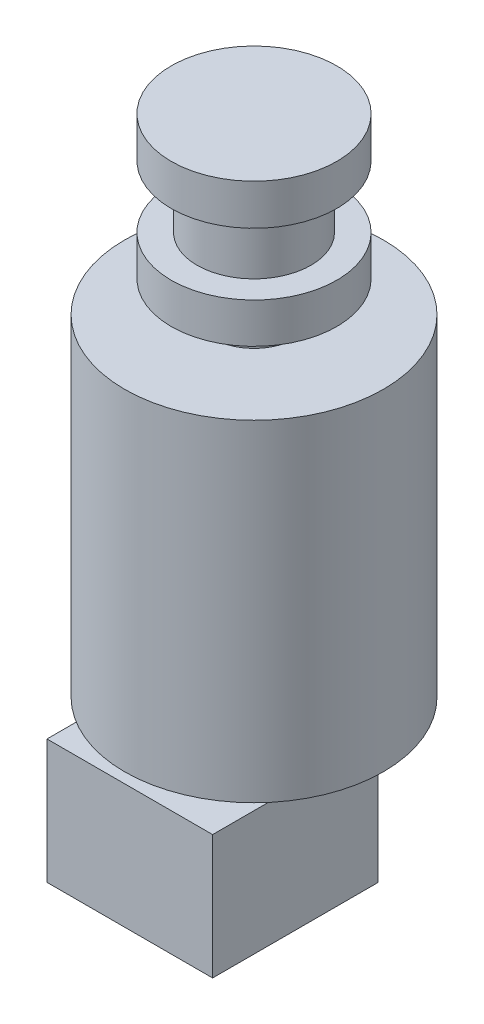
SolidWorks part; units mm, degrees
ref_plane "Plano frontal" through (0, 0, 0) normal (0, 0, 1) x (1, 0, 0)
ref_plane "Plano superior" through (0, 0, 0) normal (0, 1, 0) x (1, 0, 0)
ref_plane "Plano direito" through (0, 0, 0) normal (1, 0, 0) x (0, 0, -1)
sketch "Esboço1" plane through (0, 0, 0) normal (0, 0, 1) x (1, 0, 0)
  line L0 (0, 47.3334) -> (0, -46.585) construction
  line L1 (0, 47.3334) -> (8, 47.3334)
  line L2 (8, 47.3334) -> (8, 43.3916)
  line L3 (5.5, 43.3916) -> (5.5, 37.3916)
  line L4 (5.5, 37.3916) -> (8, 37.3916)
  line L5 (8, 37.3916) -> (8, 33.515)
  line L6 (8, 33.515) -> (4, 33.515)
  line L7 (5.5, 43.3916) -> (8, 43.3916)
  line L8 (4, 33.515) -> (4, 30.515)
  line L9 (4, 30.515) -> (12.5, 30.515)
  line L10 (12.5, 30.515) -> (12.5, -1.485)
  line L11 (12.5, -1.485) -> (2, -1.485)
  line L12 (2, -1.485) -> (0, -1.485) construction
  line L13 (2, -1.485) -> (2, -2.985)
  line L14 (2, -2.985) -> (0, -2.985)
  line L15 (0, 47.3334) -> (0, -2.985)
revolve "Revolução1" add sketch "Esboço1" angle 360 about L15
sketch "Esboço3" plane through (0, -2.985, 0) normal (0, -1, 0) x (1, 0, 0)
  line L0 (0, 0) -> (0, 4) construction
  line L2 (-8, 12) -> (8, 12)
  line L3 (-8, 12) -> (-8, -4)
  line L4 (-8, -4) -> (8, -4)
  line L5 (8, 12) -> (8, -4)
  line L6 (-8, 12) -> (8, -4) construction
  line L7 (-8, -4) -> (8, 12) construction
extrude "Ressalto-extrusão1" add sketch "Esboço3" along normal blind 12
sketch "Esboço4" plane through (0, -14.985, 0) normal (0, -1, 0) x (1, 0, 0)
  circle A0 centre (0, 0) radius 3
extrude "Ressalto-extrusão2" add sketch "Esboço4" along normal blind 6 draft 23
